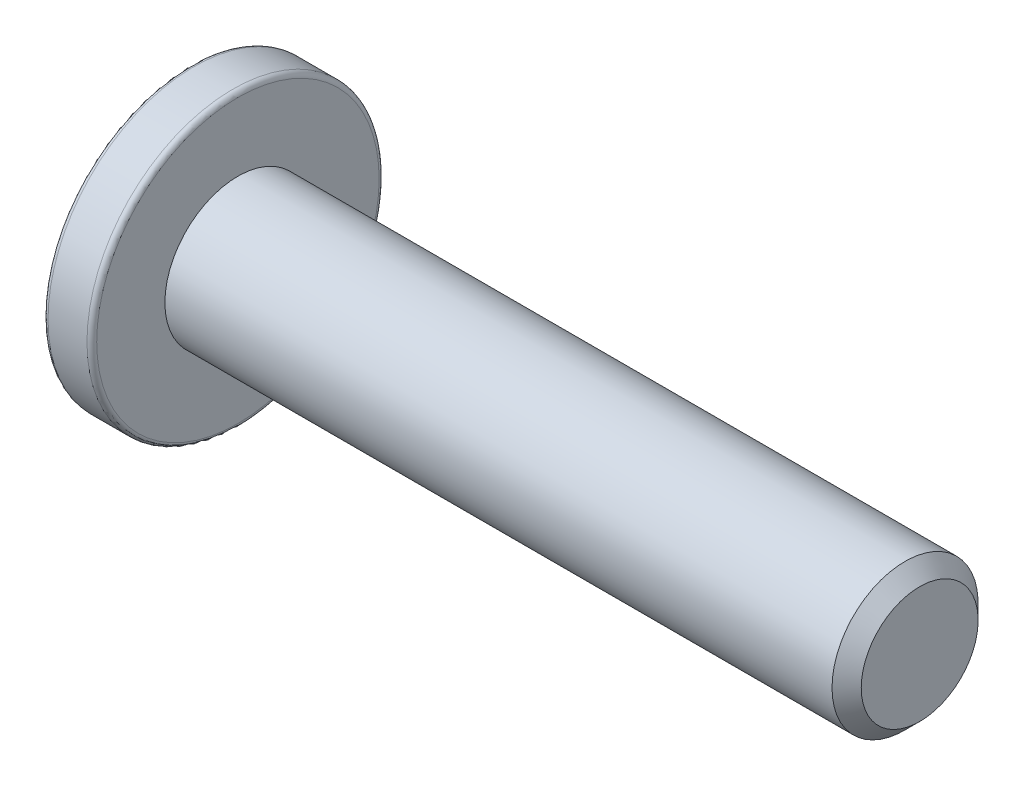
SolidWorks part; units mm, degrees
ref_plane "前视基准面" through (0, 0, 0) normal (0, 0, 1) x (1, 0, 0)
ref_plane "上视基准面" through (0, 0, 0) normal (0, 1, 0) x (1, 0, 0)
ref_plane "右视基准面" through (0, 0, 0) normal (1, 0, 0) x (0, 0, -1)
sketch "草图1" plane through (0, 0, 0) normal (0, 0, 1) x (1, 0, 0)
  line L0 (13.7, 1.5) -> (14, 1.2)
  line L1 (0, 0) -> (-1, 0)
  line L2 (0, 0) -> (0, 2.9)
  line L3 (-0.1, 3) -> (-0.9, 3)
  line L4 (-1, 0) -> (-1, 2.9)
  line L5 (0, 0) -> (14, 0)
  line L6 (0, 0) -> (0, 1.5)
  line L7 (0, 1.5) -> (13.7, 1.5)
  line L8 (14, 0) -> (14, 1.2)
  arc A0 (0, 2.9) -> (-0.1, 3) centre (-0.1, 2.9) ccw
  arc A1 (-0.9, 3) -> (-1, 2.9) centre (-0.9, 2.9) ccw
  dimension "D5" = 0.1
  dimension "D1" = 3
  dimension "D2" = 1.5
  dimension "D3" = 1
  dimension "D4" = 14
  dimension "D6" = 45
  dimension "D7" = 0.3
revolve "旋转1" add sketch "草图1" angle 360 about L5
cosmetic thread "装饰螺纹线1"
sketch "草图2" plane through (-1, 0, 0) normal (-1, 0, 0) x (0, 0, 1)
  line L1 (1, -0.5774) -> (1, 0.5774)
  line L2 (1, 0.5774) -> (0, 1.1547)
  line L3 (0, 1.1547) -> (-1, 0.5774)
  line L4 (-1, 0.5774) -> (-1, -0.5774)
  line L5 (-1, -0.5774) -> (0, -1.1547)
  line L6 (0, -1.1547) -> (1, -0.5774)
  circle A0 centre (0, 0) radius 1 construction
  dimension "D1" = 2
extrude "切除-拉伸1" cut sketch "草图2" against normal blind 0.5
